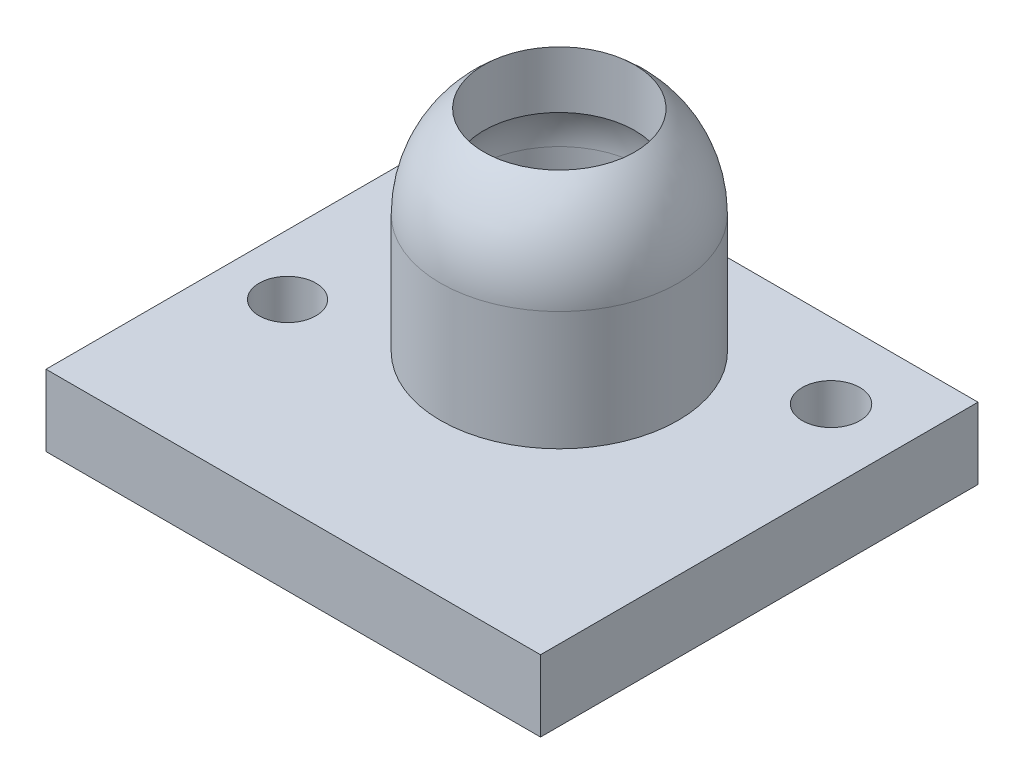
SolidWorks part; units mm, degrees
ref_plane "Front Plane" through (0, 0, 0) normal (0, 0, 1) x (1, 0, 0)
ref_plane "Top Plane" through (0, 0, 0) normal (0, 1, 0) x (1, 0, 0)
ref_plane "Right Plane" through (0, 0, 0) normal (1, 0, 0) x (0, 0, -1)
sketch "Sketch2" plane through (0, 0, 0) normal (0, 1, 0) x (1, 0, 0)
  line L6 (76.0852, 34.8007) -> (74.5852, 34.8007)
  line L8 (84.5852, 34.8007) -> (83.0852, 34.8007)
  line L10 (79.5852, 34.8007) -> (84.5852, 34.8007) construction
  arc A10 (83.0852, 34.8007) -> (76.0852, 34.8007) centre (79.5852, 34.8007) ccw
  arc A11 (84.5852, 34.8007) -> (74.5852, 34.8007) centre (79.5852, 34.8007) ccw
  point P2 (0, 0)
  point P3 (0, 0)
revolve "Revolve1" add sketch "Sketch2" angle 180 about L10
sketch "Sketch3" plane through (0, 0, 0) normal (0, -1, 0) x (1, 0, 0)
  circle A0 centre (79.5852, -34.8007) radius 5
  circle A1 centre (79.5852, -34.8007) radius 3.5
extrude "Boss-Extrude1" add sketch "Sketch3" along normal blind 5
sketch "Sketch5" plane through (0, -5, 0) normal (0, -1, 0) x (-1, 0, 0)
  circle A0 centre (-79.5852, 34.8007) radius 5 construction
  point P0 (-82.7432, 30.9242)
  point P1 (-79.5852, 34.8007)
hole_wizard "1/4 (0.2500) Dowel Hole2" positions "3DSketch2" profile "Sketch7" hole size "1/4" standard "ANSI Inch" end condition through all
sketch3d "3DSketch2"
  point P0 (79.5852, -5, -34.8007)
sketch "Sketch7" plane through (79.5852, -5, -34.8007) normal (1, 0, 0) x (0, 0, -1)
  line L0 (0, 0) -> (0, 10)
  line L1 (0, 10) -> (3.175, 10)
  line L2 (3.175, 10) -> (3.175, 0)
  line L5 (3.175, 0) -> (0, 0)
  line L11 (0, -6.35) -> (0, 107.95) construction
  dimension "Thru Hole Dia." = 6.35
  dimension "Thru Hole Depth" = 10
sketch "Sketch8" plane through (0, -5, 0) normal (0, -1, 0) x (-1, 0, 0)
  line L1 (-79.5852, 34.8007) -> (-69.4252, 34.8007)
  line L2 (-79.5852, 34.8007) -> (-79.5852, 23.3707)
  line L3 (-79.5852, 23.3707) -> (-69.4252, 23.3707)
  line L4 (-69.4252, 34.8007) -> (-69.4252, 23.3707)
  line L5 (-69.4252, 23.3707) -> (-90.2252, 23.3707)
  line L6 (-69.4252, 23.3707) -> (-69.4252, 41.7707)
  line L7 (-69.4252, 41.7707) -> (-90.2252, 41.7707)
  line L8 (-90.2252, 23.3707) -> (-90.2252, 41.7707)
  circle M3 centre (-79.5852, 34.8007) radius 5
  circle M4 centre (-79.5852, 34.8007) radius 3.5
  dimension "D1" = 10.16
  dimension "D2" = 11.43
  dimension "D3" = 20.8
  dimension "D4" = 18.4
extrude "Boss-Extrude3" add sketch "Sketch8" along normal blind 3 contours L8 L5 L2 L1 L6 L7 M3 | L2 L1 M4 M3 | L2 L1 M4 M3 | L4 L1 L2 L3 M3
sketch "Sketch10" plane through (0, -8, 0) normal (0, -1, 0) x (-1, 0, 0)
  line L1 (-69.4252, 23.3707) -> (-71.9652, 23.3707)
  line L2 (-69.4252, 23.3707) -> (-69.4252, 30.9907)
  line L3 (-69.4252, 30.9907) -> (-71.9652, 30.9907)
  line L4 (-71.9652, 23.3707) -> (-71.9652, 30.9907)
  line L5 (-69.4252, 23.3707) -> (-87.2052, 23.3707)
  line L6 (-69.4252, 23.3707) -> (-69.4252, 38.6107)
  line L7 (-69.4252, 38.6107) -> (-87.2052, 38.6107)
  line L8 (-87.2052, 23.3707) -> (-87.2052, 38.6107)
  circle A0 centre (-71.9652, 30.9907) radius 1.1932
  circle A1 centre (-87.2052, 38.6107) radius 1.2116
  dimension "D1" = 2.54
  dimension "D2" = 7.62
  dimension "D3" = 17.78
  dimension "D4" = 15.24
extrude "Cut-Extrude1" cut sketch "Sketch10" against normal through all contours L8 A1 L7 | L7 A1 L8 | L3 A0 L4 | L4 A0 L3
sketch "Sketch11" plane through (0, -8, 0) normal (0, -1, 0) x (-1, 0, 0)
  circle A0 centre (-79.5852, 34.8007) radius 4
  dimension "D1" = 8
extrude "Boss-Extrude4" add sketch "Sketch11" along normal blind 2
sketch "Sketch12" plane through (0, -10, 0) normal (0, -1, 0) x (-1, 0, 0)
  circle A0 centre (-79.5852, 34.8007) radius 1.25
  dimension "D1" = 2.5
extrude "Cut-Extrude2" cut sketch "Sketch12" against normal blind 5
sketch "Sketch13" plane through (0, -10, 0) normal (0, -1, 0) x (-1, 0, 0)
  circle A0 centre (-79.5852, 34.8007) radius 2.05
  circle A1 centre (-79.5852, 34.8007) radius 3.5
  dimension "D1" = 4.1
  dimension "D2" = 7
extrude "Cut-Extrude4" cut sketch "Sketch13" against normal blind 0.75
